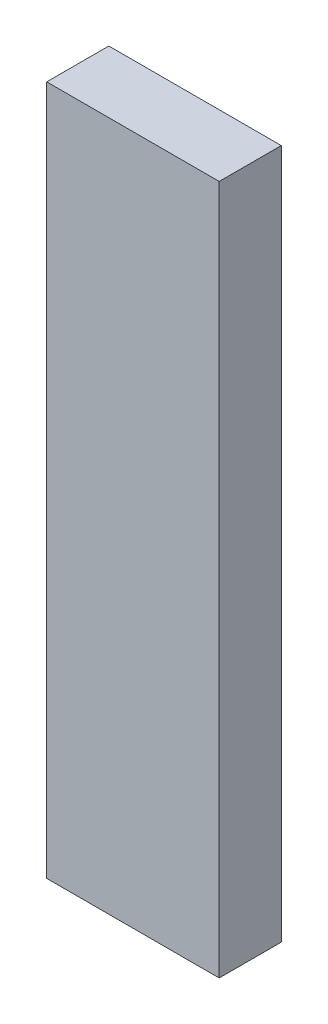
SolidWorks part; units mm, degrees
ref_plane "Front Plane" through (0, 0, 0) normal (0, 0, 1) x (1, 0, 0)
ref_plane "Top Plane" through (0, 0, 0) normal (0, 1, 0) x (1, 0, 0)
ref_plane "Right Plane" through (0, 0, 0) normal (1, 0, 0) x (0, 0, -1)
sketch "Sketch1" plane through (0, 0, 0) normal (0, 0, 1) x (1, 0, 0)
  line L1 (0, 0) -> (50, 0)
  line L2 (0, 0) -> (0, 200)
  line L3 (0, 200) -> (50, 200)
  line L4 (50, 0) -> (50, 200)
  dimension "D1" = 50
  dimension "D2" = 200
extrude "Boss-Extrude1" add sketch "Sketch1" along normal blind 18
